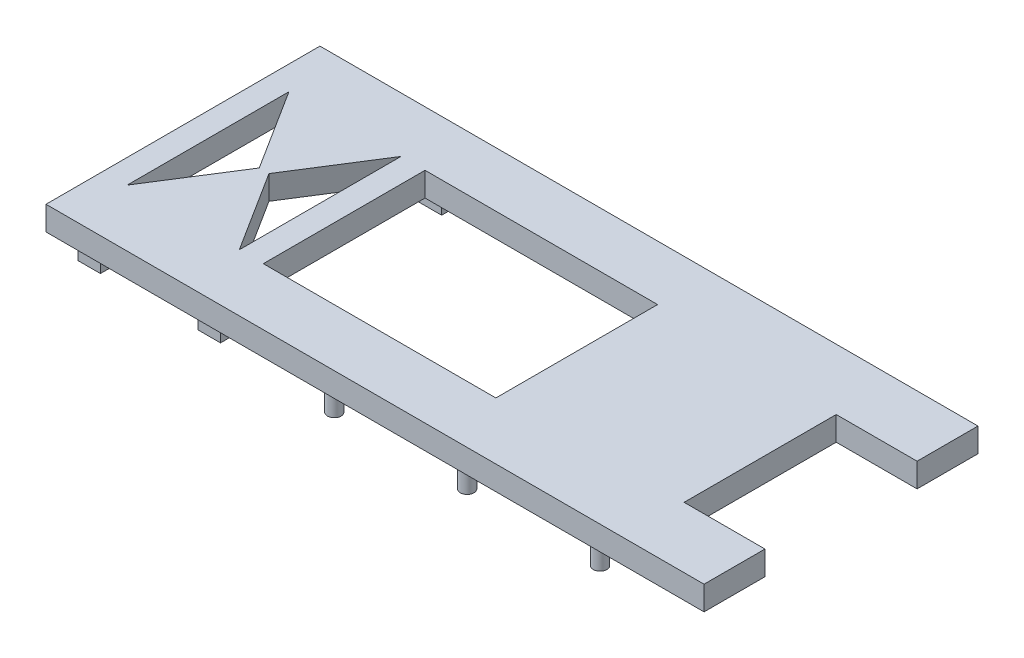
SolidWorks part; units mm, degrees
ref_plane "Front Plane" through (0, 0, 0) normal (0, 0, 1) x (1, 0, 0)
ref_plane "Top Plane" through (0, 0, 0) normal (0, 1, 0) x (1, 0, 0)
ref_plane "Right Plane" through (0, 0, 0) normal (1, 0, 0) x (0, 0, -1)
sketch "Sketch1" plane through (0, 0, 0) normal (0, 1, 0) x (1, 0, 0)
  line L1 (27.55, -13.9) -> (-27.55, -13.9)
  line L2 (27.55, -13.9) -> (27.55, 13.9)
  line L3 (27.55, 13.9) -> (-27.55, 13.9)
  line L4 (-27.55, -13.9) -> (-27.55, 13.9)
  line L5 (27.55, -13.9) -> (-27.55, 13.9) construction
  line L6 (27.55, 13.9) -> (-27.55, -13.9) construction
  point P0 (0, 0)
  dimension "D1" = 27.8
  dimension "D2" = 55.1
extrude "Boss-Extrude1" add sketch "Sketch1" along normal blind 3
sketch "Sketch2" plane through (0, 3, 0) normal (0, 1, 0) x (1, 0, 0)
  line L0 (26.7, -11.875) -> (27.55, -11.875)
  line L1 (25.525, -13.05) -> (25.525, -13.9)
  line L2 (-27.55, -13.9) -> (27.55, -13.9) construction
  line L3 (27.55, -13.9) -> (27.55, 13.9) construction
  line L4 (25.525, 13.05) -> (25.525, 13.9)
  line L5 (27.55, 13.9) -> (-27.55, 13.9) construction
  line L6 (26.7, 11.875) -> (27.55, 11.875)
  line L7 (-25.525, 13.05) -> (-25.525, 13.9)
  line L8 (-26.7, 11.875) -> (-27.55, 11.875)
  line L9 (-27.55, 13.9) -> (-27.55, -13.9) construction
  line L10 (-26.7, -11.875) -> (-27.55, -11.875)
  line L11 (-25.525, -13.05) -> (-25.525, -13.9)
  circle A0 centre (25.525, -11.875) radius 1.175
  circle A1 centre (25.525, 11.875) radius 1.175
  circle A2 centre (-25.525, 11.875) radius 1.175
  circle A3 centre (-25.525, -11.875) radius 1.175
  dimension "D1" = 2.35
  dimension "D2" = 0.85
  dimension "D4" = 2.35
  dimension "D7" = 2.35
  dimension "D10" = 2.35
  dimension "D3" = 0.85
  dimension "D5" = 0.85
  dimension "D6" = 0.85
  dimension "D8" = 0.85
  dimension "D9" = 0.85
  dimension "D11" = 0.85
  dimension "D12" = 0.85
sketch "Sketch3" plane through (0, 0, 0) normal (0, -1, 0) x (1, 0, 0)
  line L0 (-27.55, -13.9) -> (-27.55, 13.9) construction
  line L1 (-3.5, -8.25) -> (-21.15, -8.25)
  line L2 (-3.5, -8.25) -> (-3.5, 7.5)
  line L3 (-3.5, 7.5) -> (-21.15, 7.5)
  line L4 (-21.15, -8.25) -> (-21.15, 7.5)
  line L5 (-27.55, 13.9) -> (27.55, 13.9) construction
  line L6 (27.55, -13.9) -> (-27.55, -13.9) construction
  line L8 (-1.5, -10.2373) -> (-23.15, -10.2373)
  line L9 (-1.5, -10.2373) -> (-1.5, 9.9665)
  line L10 (-1.5, 9.9665) -> (-23.15, 9.9665)
  line L11 (-23.15, -10.2373) -> (-23.15, 9.9665)
  line L12 (-3.5, 7.5) -> (-21.15, 7.5)
  line L13 (-3.5, 7.5) -> (-3.5, -8.25)
  line L14 (-3.5, -8.25) -> (-21.15, -8.25)
  line L15 (-21.15, 7.5) -> (-21.15, -8.25)
  dimension "D1" = 15.75
  dimension "D2" = 17.65
  dimension "D3" = 6.4
  dimension "D4" = 6.4
  dimension "D5" = 5.65
  dimension "D6" = 2
  dimension "D7" = 20.2038
  dimension "D8" = 2
  dimension "D9" = 2.4665
extrude "Cut-Extrude1" cut sketch "Sketch3" against normal through all contours L4 L1 L2 L3 | L11 L8 L9 L10 L1 L4 L3 L2
sketch "Sketch4" plane through (0, 3, 0) normal (0, 1, 0) x (1, 0, 0)
  line L0 (-23.15, 10.2373) -> (-23.15, -9.9665)
  line L1 (-23.15, 10.2373) -> (-42.3046, 10.2373)
  line L2 (-23.15, -9.9665) -> (-42.3046, -9.9665)
  line L3 (-42.3046, 10.2373) -> (-42.3046, -9.9665)
extrude "Cut-Extrude2" cut sketch "Sketch4" against normal through all
sketch "Sketch5" plane through (0, 3, 0) normal (0, 1, 0) x (1, 0, 0)
  line L0 (27.55, 0) -> (27.55, 9.5)
  line L1 (27.55, -13.9) -> (27.55, 13.9) construction
  line L2 (27.55, 0) -> (27.55, -9.5)
  line L3 (27.55, 9.5) -> (27.55, -9.5)
  line L4 (27.55, 9.5) -> (21.55, 9.5)
  line L5 (27.55, -9.5) -> (21.55, -9.5)
  line L6 (21.55, 9.5) -> (21.55, -9.5)
  line M10 (27.55, -13.9) -> (27.55, 13.9)
  dimension "D1" = 9.5
  dimension "D2" = 9.5
  dimension "D3" = 6
extrude "Cut-Extrude3" cut sketch "Sketch5" against normal blind 10 contours L4 L6 L5 M10
sketch "Sketch7" plane through (27.55, 0, 0) normal (1, 0, 0) x (0, 0, -1)
  line L0 (9.5, 3) -> (9.5, 0)
  line L1 (9.5, 3) -> (13.9, 3)
  line L2 (9.5, 0) -> (13.9, 0)
  line L3 (13.9, 3) -> (13.9, 0)
  line L4 (13.9, 3) -> (13.9, 0) construction
  line L5 (-9.5, 3) -> (-9.5, 0)
  line L6 (-9.5, 3) -> (-13.9, 3)
  line L7 (-9.5, 0) -> (-13.9, 0)
  line L8 (-13.9, 3) -> (-13.9, 0)
  line L9 (-13.9, 3) -> (-13.9, 0) construction
  dimension "D1" = 0
  dimension "D2" = 0
extrude "Boss-Extrude2" add sketch "Sketch7" along normal blind 4.1
sketch "Sketch8" plane through (-27.55, 0, 0) normal (-1, 0, 0) x (0, 0, 1)
  line L0 (-13.9, 0) -> (-10.2373, 0)
  line L1 (-13.9, 0) -> (-13.9, 3)
  line L2 (-10.2373, 0) -> (-10.2373, 3)
  line L3 (-13.9, 3) -> (-10.2373, 3)
  line L5 (-13.9, 3) -> (-10.2373, 3) construction
  line L6 (9.9665, 0) -> (9.9665, 3)
  line L7 (9.9665, 0) -> (13.9, 0)
  line L8 (9.9665, 3) -> (13.9, 3)
  line L9 (13.9, 0) -> (13.9, 3)
  line L10 (13.9, 3) -> (13.9, 0) construction
  dimension "D1" = 0
  dimension "D2" = 0
extrude "Boss-Extrude3" add sketch "Sketch8" along normal blind 3
sketch "Sketch9" plane through (0, 0, -13.9) normal (0, 0, -1) x (-1, 0, 0)
  line L0 (-31.65, 3) -> (-31.65, 0)
  line L1 (-31.65, 3) -> (30.55, 3)
  line L2 (-31.65, 0) -> (30.55, 0)
  line L3 (30.55, 3) -> (30.55, 0)
  line L4 (30.55, 3) -> (30.55, 0) construction
  dimension "D1" = 0
extrude "Boss-Extrude4" add sketch "Sketch9" along normal blind 3.21
sketch "Sketch10" plane through (0, 0, 13.9) normal (0, 0, 1) x (1, 0, 0)
  line L0 (-30.55, 0) -> (-30.55, 3)
  line L1 (-30.55, 0) -> (31.65, 0)
  line L2 (-30.55, 3) -> (31.65, 3)
  line L3 (31.65, 0) -> (31.65, 3)
  line L4 (31.65, 3) -> (31.65, 0) construction
  dimension "D1" = 0
extrude "Boss-Extrude5" add sketch "Sketch10" along normal blind 3.21
sketch "Sketch11" plane through (0, 0, 0) normal (0, -1, 0) x (1, 0, 0)
  line L0 (-30.55, 17.11) -> (31.65, 17.11) construction
  line L1 (-30.55, 9.9665) -> (-30.55, 17.11) construction
  line L2 (31.65, -17.11) -> (-30.55, -17.11) construction
  line L3 (-30.55, -17.11) -> (-30.55, -10.2373) construction
  circle A0 centre (-16.05, 15.6) radius 0.85
  circle A1 centre (-16.05, -15.6) radius 0.85
  circle A2 centre (0.55, -15.6) radius 0.85
  circle A3 centre (0.55, 15.6) radius 0.85
  circle A4 centre (17.15, 15.6) radius 0.85
  circle A5 centre (17.15, -15.6) radius 0.85
  dimension "D1" = 1.51
  dimension "D2" = 1.7
  dimension "D4" = 1.7
  dimension "D5" = 1.51
  dimension "D6" = 14.5
  dimension "D7" = 1.7
  dimension "D8" = 31.1
  dimension "D9" = 1.51
  dimension "D10" = 1.7
  dimension "D11" = 1.51
  dimension "D12" = 31.1
  dimension "D13" = 1.7
  dimension "D14" = 47.7
  dimension "D15" = 1.51
  dimension "D16" = 1.7
  dimension "D17" = 1.51
  dimension "D18" = 47.7
  dimension "D3" = 14.5
sketch "Sketch12" plane through (-30.55, 0, 0) normal (-1, 0, 0) x (0, 0, 1)
  line L0 (-17.11, 3) -> (-17.11, 0)
  line L1 (-17.11, 3) -> (17.11, 3)
  line L2 (-17.11, 0) -> (17.11, 0)
  line L3 (17.11, 3) -> (17.11, 0)
  line L4 (17.11, 3) -> (17.11, 0) construction
  dimension "D1" = 0
extrude "Boss-Extrude7" add sketch "Sketch12" along normal blind 20
sketch "Sketch13" plane through (0, 3, 0) normal (0, 1, 0) x (1, 0, 0)
  line L0 (-33.55, 10.2373) -> (-33.55, -9.9665)
  line L1 (-1.5, 10.2373) -> (-30.55, 10.2373) construction
  line L2 (-1.5, -9.9665) -> (-30.55, -9.9665) construction
  line L3 (-30.55, -9.9665) -> (-30.55, 10.2373) construction
  line L4 (-33.55, 10.2373) -> (-39.9421, 0.1354)
  line L5 (-39.9421, 0.1354) -> (-33.55, -9.9665)
  line L6 (-47.55, 10.2373) -> (-47.55, -9.9665)
  line L7 (-47.55, -9.9665) -> (-41.1579, 0.1354)
  line L8 (-41.1579, 0.1354) -> (-47.55, 10.2373)
  dimension "D1" = 0
  dimension "D2" = 0
  dimension "D3" = 3
  dimension "D4" = 14
extrude "Cut-Extrude4" cut sketch "Sketch13" against normal through all
sketch "Sketch14" plane through (0, 0, 0) normal (0, -1, 0) x (1, 0, 0)
  line L0 (-48.45, 15.21) -> (-48.45, 12.41)
  line L1 (-48.45, 15.21) -> (-45.65, 15.21)
  line L2 (-48.45, 12.41) -> (-45.65, 12.41)
  line L3 (-45.65, 15.21) -> (-45.65, 12.41)
  line L4 (-50.55, 17.11) -> (31.65, 17.11) construction
  line L5 (-50.55, -17.11) -> (-50.55, 17.11) construction
  line L6 (31.65, -17.11) -> (-50.55, -17.11) construction
  line L7 (-48.45, -12.41) -> (-45.65, -12.41)
  line L8 (-48.45, -12.41) -> (-48.45, -15.21)
  line L9 (-48.45, -15.21) -> (-45.65, -15.21)
  line L10 (-45.65, -12.41) -> (-45.65, -15.21)
  line L12 (-33.45, 15.21) -> (-30.65, 15.21)
  line L13 (-33.45, 15.21) -> (-33.45, 12.41)
  line L14 (-33.45, 12.41) -> (-30.65, 12.41)
  line L15 (-30.65, 15.21) -> (-30.65, 12.41)
  line L17 (-33.45, -12.41) -> (-30.65, -12.41)
  line L18 (-33.45, -12.41) -> (-33.45, -15.21)
  line L19 (-33.45, -15.21) -> (-30.65, -15.21)
  line L20 (-30.65, -12.41) -> (-30.65, -15.21)
  dimension "D1" = 2.8
  dimension "D2" = 2.8
  dimension "D3" = 1.9
  dimension "D4" = 2.1
  dimension "D5" = 2.8
  dimension "D6" = 2.8
  dimension "D7" = 2.8
  dimension "D8" = 1.9
  dimension "D9" = 2.1
  dimension "D10" = 2.8
  dimension "D11" = 2.8
  dimension "D12" = 1.9
  dimension "D13" = 17.1
  dimension "D14" = 2.8
  dimension "D15" = 2.8
  dimension "D16" = 1.9
  dimension "D17" = 17.1
extrude "Boss-Extrude8" add sketch "Sketch14" along normal blind 3
extrude "Boss-Extrude9" add sketch "Sketch11" along normal blind 3
